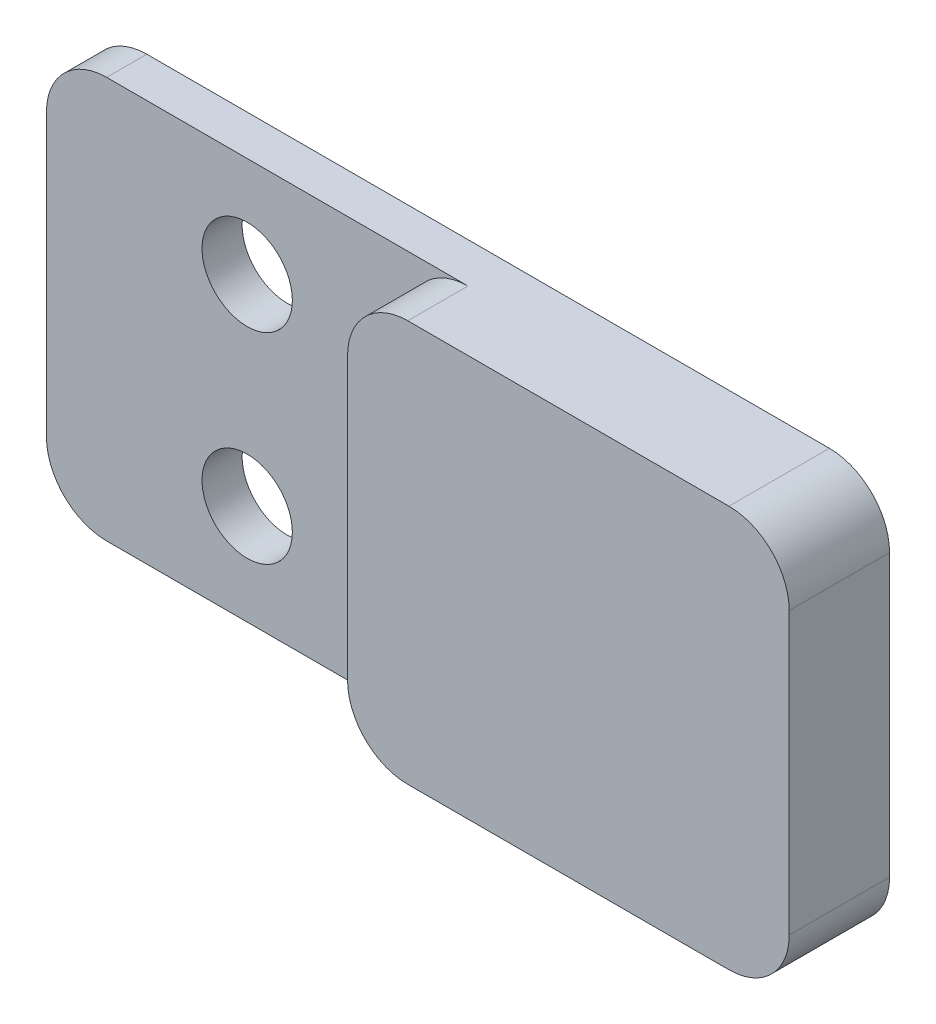
SolidWorks part; units mm, degrees
ref_plane "Płaszczyzna przednia" through (0, 0, 0) normal (0, 0, 1) x (1, 0, 0)
ref_plane "Płaszczyzna górna" through (0, 0, 0) normal (0, 1, 0) x (1, 0, 0)
ref_plane "Płaszczyzna prawa" through (0, 0, 0) normal (1, 0, 0) x (0, 0, -1)
sketch "Szkic1" plane through (0, 0, 0) normal (0, 0, 1) x (1, 0, 0)
  line L1 (-19.5054, 10.2864) -> (20.4946, 10.2864)
  line L2 (-19.5054, 10.2864) -> (-19.5054, -9.7136)
  line L3 (-19.5054, -9.7136) -> (20.4946, -9.7136)
  line L4 (20.4946, 10.2864) -> (20.4946, -9.7136)
  circle A0 centre (-9.5054, 5.2864) radius 2.25
  circle A1 centre (-9.5054, -4.7136) radius 2.25
  dimension "D3" = 4.5
  dimension "D6" = 4.5
  dimension "D1" = 40
  dimension "D2" = 20
  dimension "D4" = 10
  dimension "D5" = 5
  dimension "D7" = 10
  dimension "D8" = 5
extrude "Dodanie-wyciągnięcie1" add sketch "Szkic1" along normal blind 2
sketch "Szkic3" plane through (0, 0, 2) normal (0, 0, 1) x (1, 0, 0)
  line L0 (-19.5054, 10.2864) -> (20.4946, 10.2864) construction
  line L1 (-1.5054, 10.2864) -> (20.4946, 10.2864)
  line L2 (-1.5054, 10.2864) -> (-1.5054, -9.7136)
  line L3 (-1.5054, -9.7136) -> (20.4946, -9.7136)
  line L4 (20.4946, 10.2864) -> (20.4946, -9.7136)
  line L5 (-19.5054, 10.2864) -> (-19.5054, -9.7136) construction
  dimension "D1" = 20
  dimension "D2" = 18
  dimension "D3" = 22
extrude "Dodanie-wyciągnięcie3" add sketch "Szkic3" along normal blind 3
fillet "Zaokrąglenie1" radius 3 6 edges at (-19.5054, -9.7136, 1) (20.4946, -9.7136, 2.5) (20.4946, 10.2864, 2.5) (-19.5054, 10.2864, 1) (-1.5054, -9.7136, 3.5) (-1.5054, 10.2864, 3.5)
